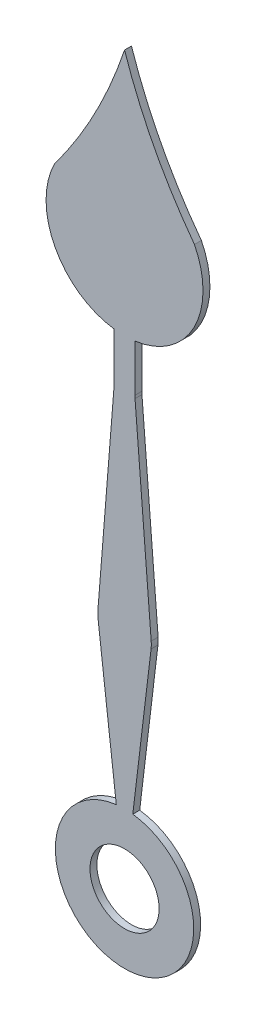
SolidWorks part; units mm, degrees
ref_plane "Front Plane" through (0, 0, 0) normal (0, 0, 1) x (1, 0, 0)
ref_plane "Top Plane" through (0, 0, 0) normal (0, 1, 0) x (1, 0, 0)
ref_plane "Right Plane" through (0, 0, 0) normal (1, 0, 0) x (0, 0, -1)
sketch "Sketch1" plane through (0, 0, 0) normal (0, 0, 1) x (1, 0, 0)
  line L0 (0, 0) -> (0, 21) construction
  line L1 (-0.2384, 1.9857) -> (-0.7668, 6.3865)
  line L2 (-0.7708, 6.5856) -> (-0.3032, 12.424)
  line L3 (-0.3, 12.5038) -> (-0.3, 13.8629)
  line L4 (0.2384, 1.9857) -> (0.7668, 6.3865)
  line L5 (0.7708, 6.5856) -> (0.3032, 12.424)
  line L6 (0.3, 12.5038) -> (0.3, 13.8629)
  circle A0 centre (0, 0) radius 1
  arc A1 (-0.2384, 1.9857) -> (0.2384, 1.9857) centre (0, 0) ccw
  arc A2 (-2.0204, 17.1431) -> (-0.3, 13.8629) centre (0, 16.1115) ccw
  arc A3 (-0.7668, 6.3865) -> (-0.7708, 6.5856) centre (0.2261, 6.5057) cw
  arc A4 (-0.3032, 12.424) -> (-0.3, 12.5038) centre (-1.3, 12.5038) ccw
  arc A5 (-2.0204, 17.1431) -> (0, 21) centre (-12.9954, 25.3498) ccw
  arc A6 (0.7668, 6.3865) -> (0.7708, 6.5856) centre (-0.2261, 6.5057) ccw
  arc A7 (0.3032, 12.424) -> (0.3, 12.5038) centre (1.3, 12.5038) cw
  arc A8 (2.0204, 17.1431) -> (0.3, 13.8629) centre (0, 16.1115) cw
  arc A9 (2.0204, 17.1431) -> (0, 21) centre (12.9954, 25.3498) cw
  dimension "D1" = 2
  dimension "D2" = 4
  dimension "D4" = 1
  dimension "D5" = 1
  dimension "D6" = 0.6
extrude "Boss-Extrude1" add sketch "Sketch1" along normal blind 0.2
